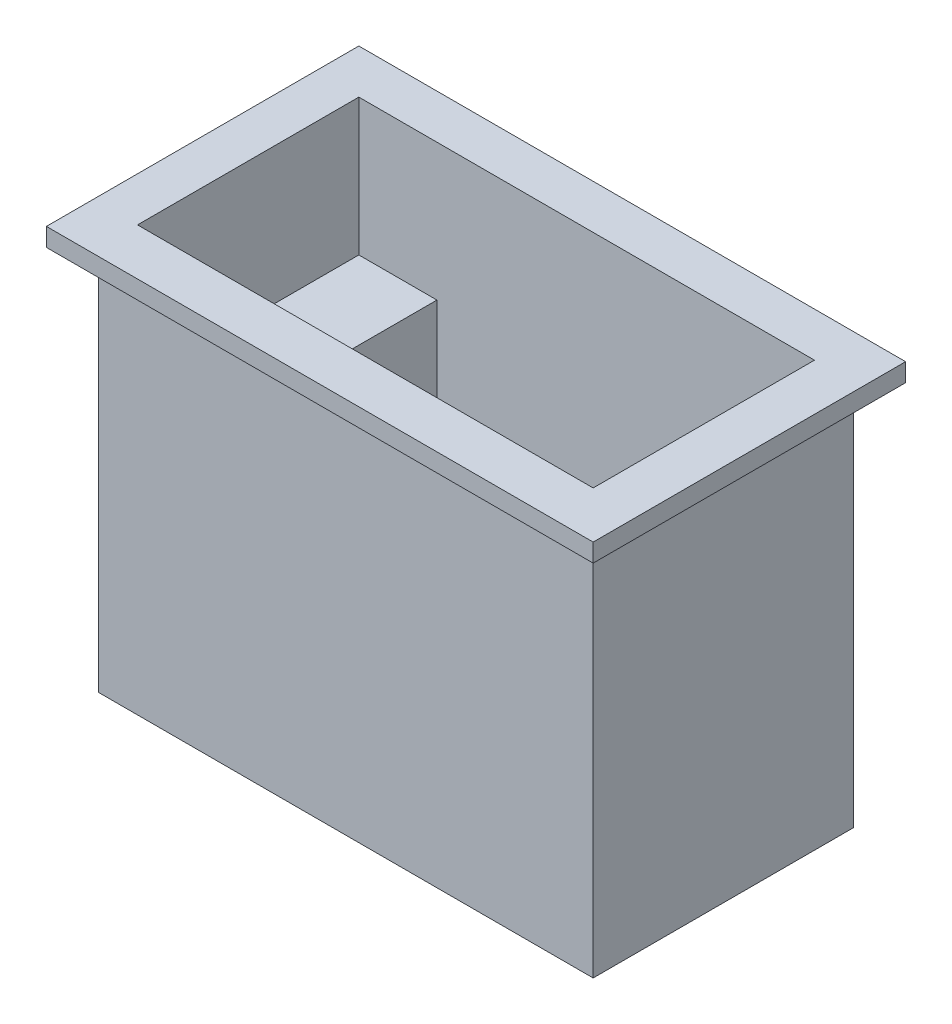
SolidWorks part; units mm, degrees
ref_plane "Front Plane" through (0, 0, 0) normal (0, 0, 1) x (1, 0, 0)
ref_plane "Top Plane" through (0, 0, 0) normal (0, 1, 0) x (1, 0, 0)
ref_plane "Right Plane" through (0, 0, 0) normal (1, 0, 0) x (0, 0, -1)
sketch "Sketch1" plane through (0, 0, 0) normal (0, 1, 0) x (1, 0, 0)
  line L1 (-10.4, 5.9429) -> (27.6, 5.9429)
  line L2 (-10.4, 5.9429) -> (-10.4, -14.0571)
  line L3 (-10.4, -14.0571) -> (27.6, -14.0571)
  line L4 (27.6, 5.9429) -> (27.6, -14.0571)
  dimension "D1" = 38
  dimension "D2" = 20
extrude "Boss-Extrude1" add sketch "Sketch1" along normal blind 31
sketch "Sketch2" plane through (0, 31, 0) normal (0, 1, 0) x (1, 0, 0)
  line L0 (27.6, 5.9429) -> (-10.4, 5.9429) construction
  line L1 (-9, 4.5429) -> (26, 4.5429)
  line L2 (-9, 4.5429) -> (-9, -12.4571)
  line L3 (-9, -12.4571) -> (26, -12.4571)
  line L4 (26, 4.5429) -> (26, -12.4571)
  line L5 (-10.4, 5.9429) -> (-10.4, -14.0571) construction
  dimension "D1" = 35
  dimension "D2" = 17
  dimension "D3" = 1.4
  dimension "D4" = 1.4
extrude "Cut-Extrude1" cut sketch "Sketch2" against normal blind 28
sketch "Sketch3" plane through (0, 3, 0) normal (0, 1, 0) x (1, 0, 0)
  line L0 (-9, -12.4571) -> (26, -12.4571) construction
  line L1 (-9, 4.5429) -> (-3, 4.5429)
  line L2 (-9, 4.5429) -> (-9, -12.4571)
  line L3 (-9, -12.4571) -> (-3, -12.4571)
  line L4 (-3, 4.5429) -> (-3, -12.4571)
  line L5 (26, 4.5429) -> (-9, 4.5429) construction
  line L6 (20, 4.5429) -> (26, 4.5429)
  line L7 (20, 4.5429) -> (20, -12.4571)
  line L8 (20, -12.4571) -> (26, -12.4571)
  line L9 (26, 4.5429) -> (26, -12.4571)
  dimension "D1" = 6
  dimension "D2" = 6
extrude "Boss-Extrude2" add sketch "Sketch3" along normal blind 17.5
sketch "Sketch4" plane through (0, 31, 0) normal (0, 1, 0) x (1, 0, 0)
  line L1 (-10.4, 5.9429) -> (27.6, 5.9429)
  line L2 (-10.4, 5.9429) -> (-10.4, -14.0571)
  line L3 (-10.4, -14.0571) -> (27.6, -14.0571)
  line L4 (27.6, 5.9429) -> (27.6, -14.0571)
extrude "Extrude-Thin2" add sketch "Sketch4" against normal blind 1.4 thin thin type one direction wall 2
sketch "Sketch5" plane through (0, 20.5, 0) normal (0, 1, 0) x (1, 0, 0)
  line L0 (-3, -12.4571) -> (-3, 4.5429) construction
  circle A0 centre (-5.5, -3.8921) radius 1
  dimension "D1" = 2
  dimension "D2" = 2.5
extrude "Cut-Extrude2" cut sketch "Sketch5" against normal blind 3
sketch "Sketch6" plane through (0, 20.5, 0) normal (0, 1, 0) x (1, 0, 0)
  circle A0 centre (22.9531, -4.1157) radius 1
  dimension "D1" = 2
extrude "Cut-Extrude3" cut sketch "Sketch6" against normal blind 3
sketch "Sketch7" plane through (-3, 0, 0) normal (1, 0, 0) x (0, 0, -1)
  line L1 (-1.0391, 4.0414) -> (-9.0391, 4.0414)
  line L2 (-1.0391, 4.0414) -> (-1.0391, 7.0414)
  line L3 (-1.0391, 7.0414) -> (-9.0391, 7.0414)
  line L4 (-9.0391, 4.0414) -> (-9.0391, 7.0414)
  dimension "D1" = 8
  dimension "D2" = 3
extrude "Cut-Extrude4" cut sketch "Sketch7" against normal blind 10
sketch "Sketch8" plane through (0, 3, 0) normal (0, 1, 0) x (1, 0, 0)
  line L1 (-0.0887, -7.5845) -> (17.9113, -7.5845)
  line L2 (-0.0887, -7.5845) -> (-0.0887, 1.4155)
  line L3 (-0.0887, 1.4155) -> (17.9113, 1.4155)
  line L4 (17.9113, -7.5845) -> (17.9113, 1.4155)
  dimension "D1" = 9
  dimension "D2" = 18
extrude "Cut-Extrude5" cut sketch "Sketch8" against normal blind 2
sketch "Sketch9" plane through (0, 1, 0) normal (0, 1, 0) x (1, 0, 0)
  circle A0 centre (8.6887, -3.1706) radius 3.725
  circle A3 centre (1.9637, -3.1706) radius 0.7
  circle A4 centre (15.4137, -3.1706) radius 0.7
  point P6 (8.6887, -3.1706)
  dimension "D1" = 7.45
  dimension "D2" = 3
  dimension "D3" = 3
extrude "Cut-Extrude6" cut sketch "Sketch9" against normal blind 4
fillet "Fillet1" radius 4 4 edges at (17.9113, 2, -1.4155) (17.9113, 2, 7.5845) (-0.0887, 2, -1.4155) (-0.0887, 2, 7.5845)
